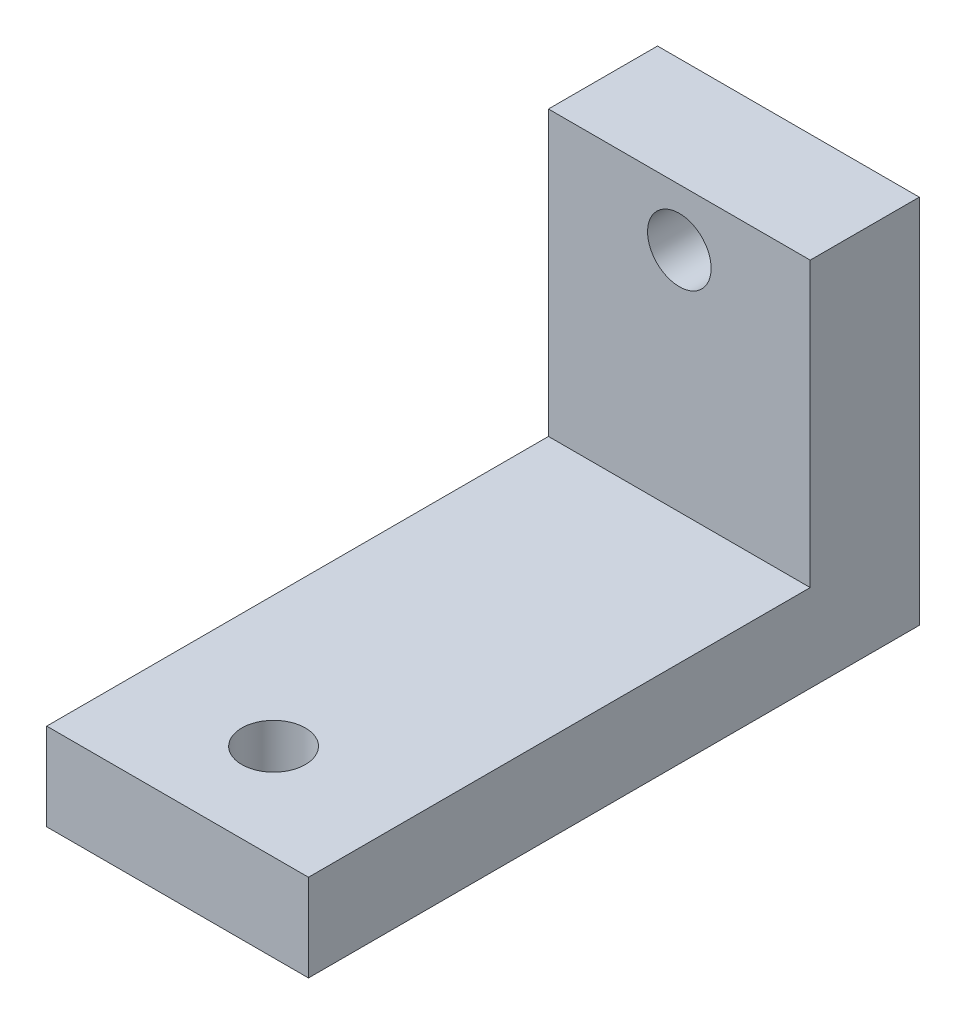
SolidWorks part; units mm, degrees
ref_plane "Front Plane" through (0, 0, 0) normal (0, 0, 1) x (1, 0, 0)
ref_plane "Top Plane" through (0, 0, 0) normal (0, 1, 0) x (1, 0, 0)
ref_plane "Right Plane" through (0, 0, 0) normal (1, 0, 0) x (0, 0, -1)
sketch "Sketch1" plane through (0, 0, 0) normal (0, 1, 0) x (1, 0, 0)
  line L1 (-7.62, 1.9106) -> (7.62, 1.9106)
  line L2 (-7.62, 1.9106) -> (-7.62, -4.4394)
  line L3 (-7.62, -4.4394) -> (7.62, -4.4394)
  line L4 (7.62, 1.9106) -> (7.62, -4.4394)
  dimension "D1" = 15.24
  dimension "D2" = 7.62
  dimension "D3" = 6.35
extrude "Boss-Extrude1" add sketch "Sketch1" along normal blind 21.59
sketch "Sketch2" plane through (0, 0, 4.4394) normal (0, 0, 1) x (1, 0, 0)
  line L0 (7.62, 21.59) -> (7.62, 0) construction
  line L1 (-7.62, 0) -> (7.62, 0)
  line L2 (-7.62, 0) -> (-7.62, 5.08)
  line L3 (-7.62, 5.08) -> (7.62, 5.08)
  line L4 (7.62, 0) -> (7.62, 5.08)
  dimension "D1" = 5.08
extrude "Boss-Extrude2" add sketch "Sketch2" along normal blind 29.21
sketch "Sketch3" plane through (0, 0, 4.4394) normal (0, 0, 1) x (1, 0, 0)
  line L0 (-7.62, 0) -> (7.62, 0) construction
  circle A0 centre (0, 18.288) radius 1.6131
  dimension "D1" = 18.288
  dimension "D2" = 3.2262
sketch "Sketch4" plane through (0, 5.08, 0) normal (0, 1, 0) x (1, 0, 0)
  line L0 (7.62, 1.9106) -> (-7.62, 1.9106) construction
  circle A0 centre (0, -28.0614) radius 1.2063
  dimension "D1" = 29.972
hole_wizard "M3 Clearance Hole1" positions "Sketch5" profile "Sketch6" hole size "M3" standard "ANSI Metric"
sketch "Sketch5" plane through (0, 5.08, 0) normal (0, 1, 0) x (1, 0, 0)
  point P0 (0, -28.0614)
sketch "Sketch6" plane through (0, 5.08, 28.0614) normal (1, 0, 0) x (0, 0, 1)
  line L0 (0, 0) -> (0, 26.5116)
  line L1 (0, 26.5116) -> (1.85, 25.4)
  line L2 (1.85, 25.4) -> (1.85, 0)
  line L5 (1.85, 0) -> (0, 0)
  line L10 (0, 26.5116) -> (-1.85, 25.4) construction
  line L11 (0, -6.35) -> (0, 107.95) construction
  dimension "Hole Dia." = 3.7
  dimension "Hole Depth" = 25.4
  dimension "Drill Angle" = 118
hole_wizard "M3 Clearance Hole2" positions "Sketch7" profile "Sketch8" hole size "M3" standard "ANSI Metric"
sketch "Sketch7" plane through (0, 0, 4.4394) normal (0, 0, 1) x (1, 0, 0)
  point P0 (0, 18.288)
sketch "Sketch8" plane through (0, 18.288, 4.4394) normal (1, 0, 0) x (0, -1, 0)
  line L0 (0, 0) -> (0, 26.5116)
  line L1 (0, 26.5116) -> (1.85, 25.4)
  line L2 (1.85, 25.4) -> (1.85, 0)
  line L5 (1.85, 0) -> (0, 0)
  line L10 (0, 26.5116) -> (-1.85, 25.4) construction
  line L11 (0, -6.35) -> (0, 107.95) construction
  dimension "Hole Dia." = 3.7
  dimension "Hole Depth" = 25.4
  dimension "Drill Angle" = 118
